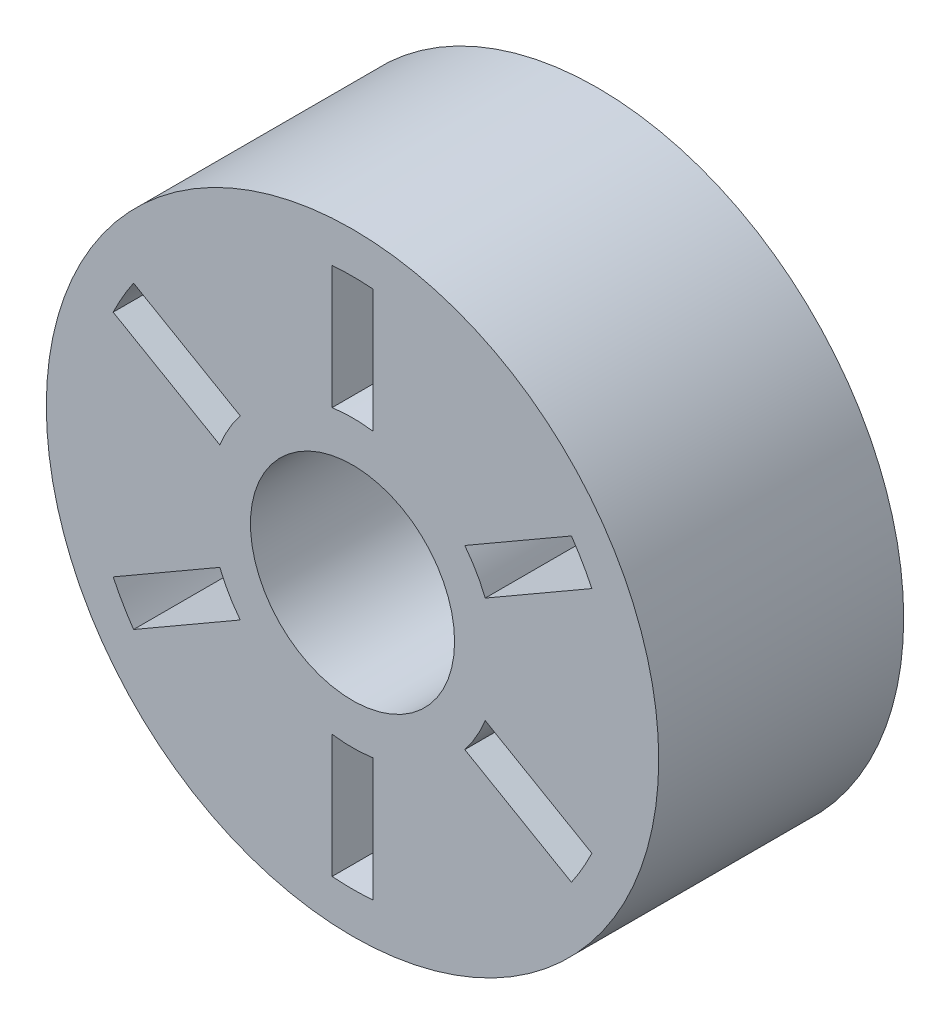
SolidWorks part; units mm, degrees
material "1060 Alloy"
ref_plane "Front Plane" through (0, 0, 0) normal (0, 0, 1) x (1, 0, 0)
ref_plane "Top Plane" through (0, 0, 0) normal (0, 1, 0) x (1, 0, 0)
ref_plane "Right Plane" through (0, 0, 0) normal (1, 0, 0) x (0, 0, -1)
sketch "Sketch2" plane through (0, 0, 0) normal (0, 0, 1) x (1, 0, 0)
  circle A0 centre (0, 0) radius 37.5
  circle A1 centre (0, 0) radius 12.5
  dimension "D1" = 75
  dimension "D2" = 25
extrude "Boss-Extrude1" add sketch "Sketch2" along normal blind 30
sketch "Sketch5" plane through (0, 0, 30) normal (0, 0, 1) x (1, 0, 0)
  line L0 (2.5, 32.4037) -> (2.5, 17.3205)
  line L1 (0, -16.5) -> (0, 16.5) construction
  line L2 (-2.5, 32.4037) -> (-2.5, 17.3205)
  circle A2 centre (0, 0) radius 17.5
  arc A3 (2.5, 17.3205) -> (-2.5, 17.3205) centre (0, 0) ccw
  circle A5 centre (0, 0) radius 32.5
  arc A6 (2.5, 32.4037) -> (-2.5, 32.4037) centre (0, 0) ccw
  dimension "D3" = 5
  dimension "D1" = 5
  dimension "D2" = 5
extrude "Cut-Extrude1" cut sketch "Sketch5" against normal through all
pattern_circular "CirPattern1" count 6 over 360 about axis through (0, 0, 0) along (0, 0, 1) of "Cut-Extrude1"
